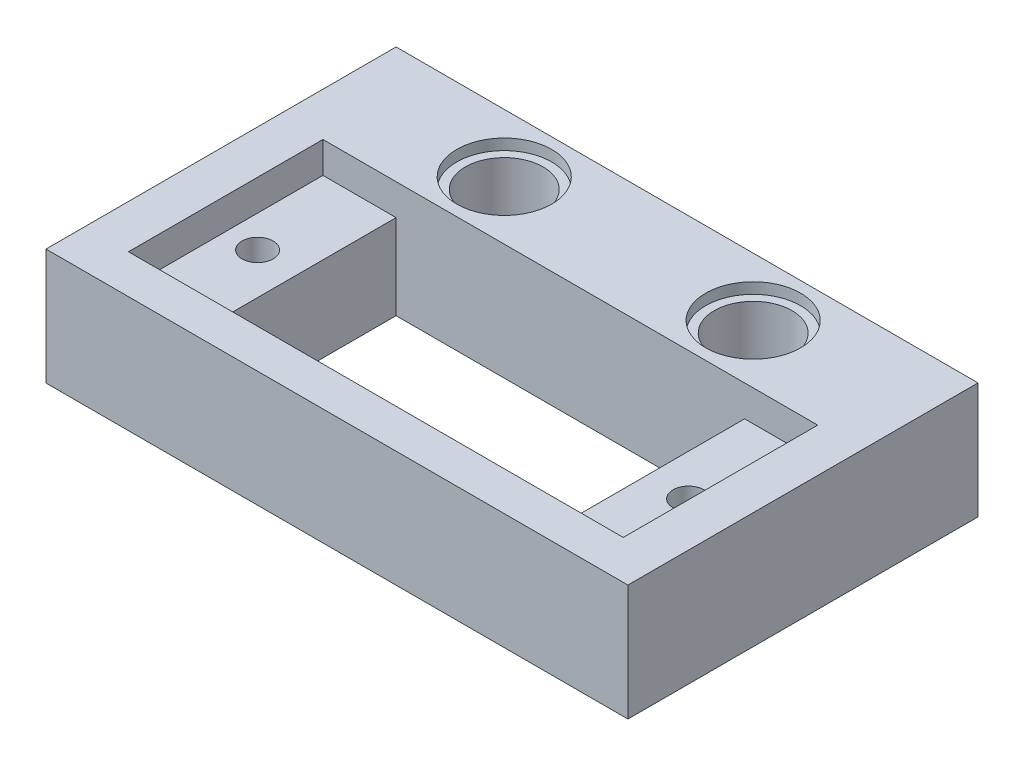
SolidWorks part; units mm, degrees
ref_plane "Front Plane" through (0, 0, 0) normal (0, 0, 1) x (1, 0, 0)
ref_plane "Top Plane" through (0, 0, 0) normal (0, 1, 0) x (1, 0, 0)
ref_plane "Right Plane" through (0, 0, 0) normal (1, 0, 0) x (0, 0, -1)
sketch "Sketch1" plane through (0, 0, 0) normal (0, 1, 0) x (1, 0, 0)
  line L0 (0, 14.5365) -> (0, -17.0646) construction
  line L1 (-33.4738, 0) -> (30.103, 0) construction
  line L2 (-18.7, 13.75) -> (-18.7, -8.75)
  line L3 (-11.2, 6.25) -> (11.2, 6.25)
  line L4 (-11.2, 6.25) -> (-11.2, -6.25)
  line L5 (-11.2, -6.25) -> (11.2, -6.25)
  line L6 (11.2, 6.25) -> (11.2, -6.25)
  line L7 (-11.2, 6.25) -> (11.2, -6.25) construction
  line L8 (-11.2, -6.25) -> (11.2, 6.25) construction
  line L9 (-18.7, -8.75) -> (18.7, -8.75)
  line L10 (18.7, -8.75) -> (18.7, 13.75)
  line L11 (18.7, 13.75) -> (-18.7, 13.75)
  circle A0 centre (13.85, 0) radius 1
  circle A1 centre (-13.85, 0) radius 1
  point P5 (0, 0)
  point P18 (18.7, 2.5)
  dimension "D3" = 2
  dimension "D1" = 12.5
  dimension "D2" = 22.4
  dimension "D4" = 27.7
  dimension "D5" = 7.5
  dimension "D6" = 7.5
  dimension "D7" = 7.5
  dimension "D8" = 2.5
extrude "Boss-Extrude1" add sketch "Sketch1" against normal blind 7.46
sketch "Sketch2" plane through (0, 0, 0) normal (0, 1, 0) x (1, 0, 0)
  line L0 (0, 6.25) -> (0, -6.25) construction
  line L1 (11.2, 6.25) -> (-11.2, 6.25) construction
  line L2 (-11.2, -6.25) -> (11.2, -6.25) construction
  line L3 (-18.7, 0) -> (18.7, 0) construction
  line L4 (-18.7, 13.75) -> (-18.7, -8.75) construction
  line L5 (18.7, -8.75) -> (18.7, 13.75) construction
  line L7 (-15.9, 6.25) -> (15.9, 6.25)
  line L8 (-15.9, 6.25) -> (-15.9, -6.25)
  line L9 (-15.9, -6.25) -> (15.9, -6.25)
  line L10 (15.9, 6.25) -> (15.9, -6.25)
  line L11 (-15.9, 6.25) -> (15.9, -6.25) construction
  line L12 (-15.9, -6.25) -> (15.9, 6.25) construction
  point P13 (0, 0)
  dimension "D1" = 12.5
  dimension "D2" = 31.8
extrude "Cut-Extrude1" cut sketch "Sketch2" against normal blind 2
sketch "Sketch3" plane through (0, 0, 0) normal (0, 1, 0) x (1, 0, 0)
  line L0 (0, 6.25) -> (0, 13.75) construction
  line L1 (15.9, 6.25) -> (-15.9, 6.25) construction
  line L2 (18.7, 13.75) -> (-18.7, 13.75) construction
  line L3 (0, 10) -> (18.7, 10) construction
  line L4 (18.7, -8.75) -> (18.7, 13.75) construction
  circle A0 centre (8, 10) radius 2.5
  circle A1 centre (-8, 10) radius 2.5
  dimension "D1" = 5
  dimension "D2" = 8
extrude "Cut-Extrude2" cut sketch "Sketch3" against normal through all
sketch "Sketch4" plane through (0, 0, 0) normal (0, 1, 0) x (1, 0, 0)
  circle A0 centre (-8, 10) radius 3.05
  circle A1 centre (8, 10) radius 3.05
  dimension "D1" = 6.1
  dimension "D2" = 6.1
extrude "Cut-Extrude3" cut sketch "Sketch4" against normal blind 0.7
sketch "Sketch5" plane through (0, -7.46, 0) normal (0, -1, 0) x (-1, 0, 0)
  circle A0 centre (-8, 10) radius 3.05
  circle A1 centre (8, 10) radius 3.05
  dimension "D1" = 6.1
  dimension "D2" = 6.1
extrude "Cut-Extrude4" cut sketch "Sketch5" against normal blind 0.7
